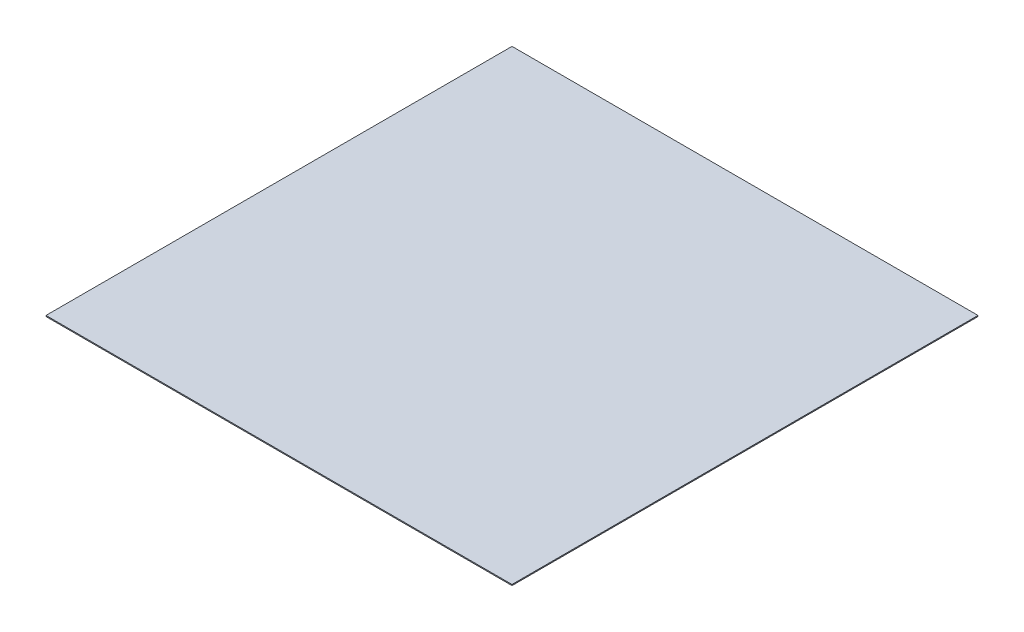
SolidWorks part; units mm, degrees
material "STYCAST 2850FT/Catalyst 23LV"
ref_plane "Front Plane" through (0, 0, 0) normal (0, 0, 1) x (1, 0, 0)
ref_plane "Top Plane" through (0, 0, 0) normal (0, 1, 0) x (1, 0, 0)
ref_plane "Right Plane" through (0, 0, 0) normal (1, 0, 0) x (0, 0, -1)
sketch "Sketch1" plane through (0, 0, 0) normal (0, 1, 0) x (1, 0, 0)
  line L1 (-57, -57) -> (57, -57)
  line L2 (-57, -57) -> (-57, 57)
  line L3 (-57, 57) -> (57, 57)
  line L4 (57, -57) -> (57, 57)
  line L5 (-57, -57) -> (57, 57) construction
  line L6 (-57, 57) -> (57, -57) construction
  point P0 (0, 0)
  dimension "D1" = 114
extrude "Boss-Extrude1" add sketch "Sketch1" along normal mid plane 0.25
equation "\"panel_width\"= 114mm"
equation "\"finger_joint_width\" = 25mm"
equation "\"D1@Sketch1\"=\"panel_width\""
